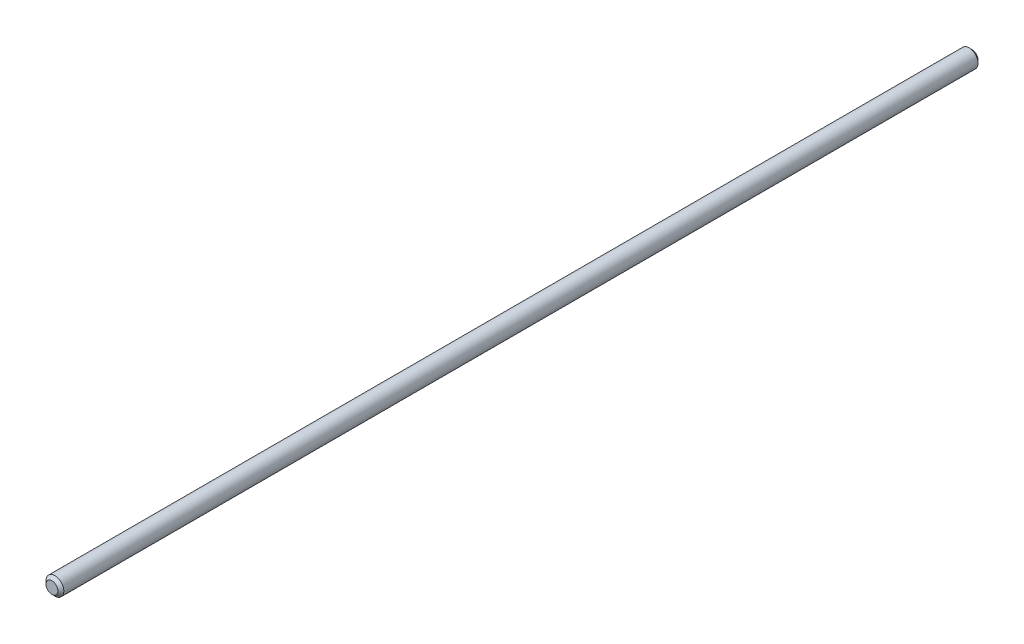
SolidWorks part; units mm, degrees
material "Plain Carbon Steel"
ref_plane "Спереди" through (0, 0, 0) normal (0, 0, 1) x (1, 0, 0)
ref_plane "Сверху" through (0, 0, 0) normal (0, 1, 0) x (1, 0, 0)
ref_plane "Справа" through (0, 0, 0) normal (1, 0, 0) x (0, 0, -1)
sketch "Sketch1" plane through (0, 0, 0) normal (0, 0, 1) x (1, 0, 0)
  circle A0 centre (0, 0) radius 3
  dimension "D1" = 6
extrude "Boss-Extrude1" add sketch "Sketch1" along normal blind 310
chamfer "Chamfer1" distance 1 angle 45 2 edges at (3, 0, 310) (3, 0, 0)
